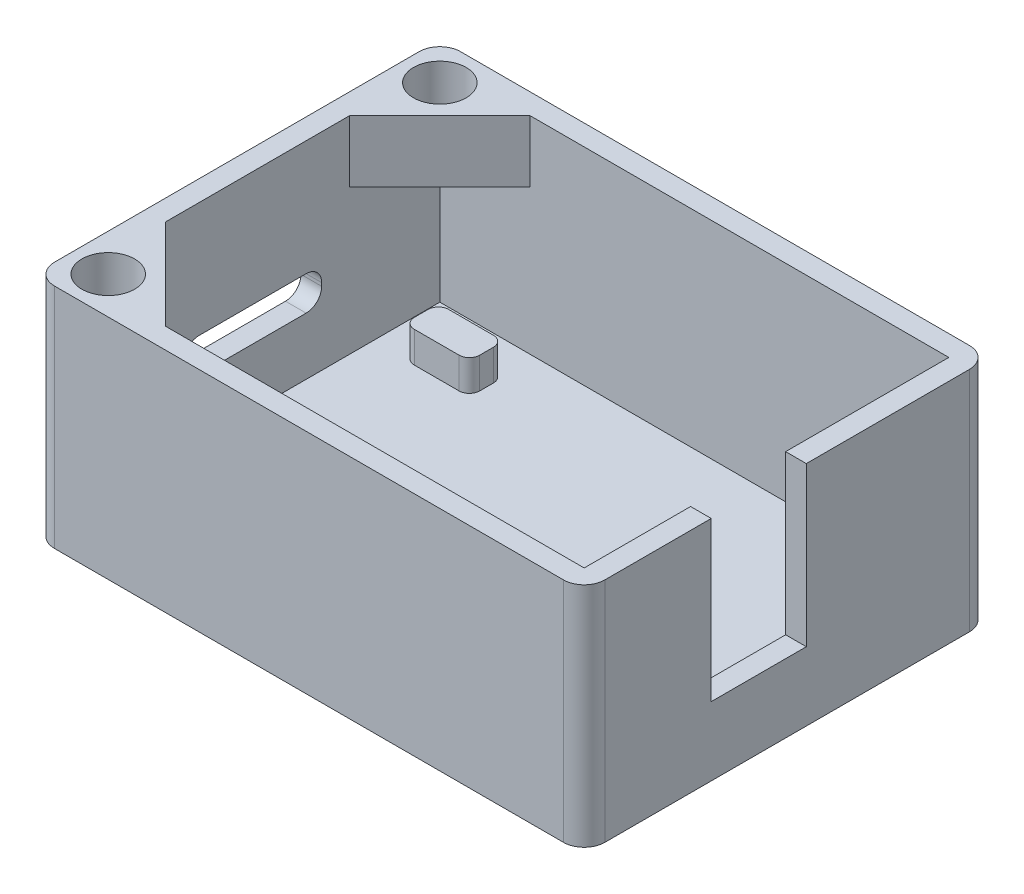
SolidWorks part; units mm, degrees
ref_plane "Front Plane" through (0, 0, 0) normal (0, 0, 1) x (1, 0, 0)
ref_plane "Top Plane" through (0, 0, 0) normal (0, 1, 0) x (1, 0, 0)
ref_plane "Right Plane" through (0, 0, 0) normal (1, 0, 0) x (0, 0, -1)
sketch "Sketch1" plane through (0, 0, 0) normal (0, 1, 0) x (1, 0, 0)
  line L0 (-26.63, 19.645) -> (26.63, 19.645)
  line L1 (-24.13, 17.145) -> (24.13, 17.145) construction
  line L2 (-24.13, 17.145) -> (-24.13, -17.145) construction
  line L3 (-24.13, -17.145) -> (24.13, -17.145) construction
  line L4 (24.13, 17.145) -> (24.13, -17.145) construction
  line L5 (-24.13, 17.145) -> (24.13, -17.145) construction
  line L6 (-24.13, -17.145) -> (24.13, 17.145) construction
  line L7 (26.63, 19.645) -> (26.63, -19.645)
  line L8 (-26.63, -19.645) -> (26.63, -19.645)
  line L9 (-26.63, 19.645) -> (-26.63, -19.645)
  point P0 (0, 0)
  dimension "D1" = 48.26
  dimension "D2" = 34.29
  dimension "D3" = 2.5
extrude "Boss-Extrude1" add sketch "Sketch1" along normal blind 2
sketch "Sketch2" plane through (0, 2, 0) normal (0, 1, 0) x (1, 0, 0)
  line L0 (-24.63, 17.645) -> (24.63, 17.645)
  line L1 (-26.63, 19.645) -> (26.63, 19.645)
  line L2 (-26.63, 19.645) -> (-26.63, -19.645)
  line L3 (-26.63, -19.645) -> (26.63, -19.645)
  line L4 (26.63, 19.645) -> (26.63, -19.645)
  line L5 (-26.63, 19.645) -> (26.63, -19.645) construction
  line L6 (-26.63, -19.645) -> (26.63, 19.645) construction
  line L7 (24.63, 17.645) -> (24.63, -17.645)
  line L8 (-24.63, -17.645) -> (24.63, -17.645)
  line L9 (-24.63, 17.645) -> (-24.63, -17.645)
  point P0 (0, 0)
  dimension "D1" = 2
extrude "Boss-Extrude2" add sketch "Sketch2" along normal blind 20
sketch "Sketch3" plane through (0, 2, 0) normal (0, 1, 0) x (1, 0, 0)
  line L0 (0, 26.1513) -> (0, -23.4046) construction
  line L1 (-20.59, 14.4658) -> (-16.261, 14.4658)
  line L2 (-21.59, 13.4658) -> (-21.59, 12.1374)
  line L3 (-20.59, 11.1374) -> (-16.261, 11.1374)
  line L4 (-15.261, 13.4658) -> (-15.261, 12.1374)
  line L5 (15.261, 13.4658) -> (15.261, 12.1374)
  line L6 (20.59, 11.1374) -> (16.261, 11.1374)
  line L7 (21.59, 13.4658) -> (21.59, 12.1374)
  line L8 (20.59, 14.4658) -> (16.261, 14.4658)
  arc A2 (-21.59, 12.1374) -> (-20.59, 11.1374) centre (-20.59, 12.1374) ccw
  arc A3 (-16.261, 14.4658) -> (-15.261, 13.4658) centre (-16.261, 13.4658) cw
  arc A4 (-15.261, 12.1374) -> (-16.261, 11.1374) centre (-16.261, 12.1374) cw
  arc A5 (-21.59, 13.4658) -> (-20.59, 14.4658) centre (-20.59, 13.4658) cw
  arc A6 (21.59, 13.4658) -> (20.59, 14.4658) centre (20.59, 13.4658) ccw
  arc A7 (15.261, 12.1374) -> (16.261, 11.1374) centre (16.261, 12.1374) ccw
  arc A8 (16.261, 14.4658) -> (15.261, 13.4658) centre (16.261, 13.4658) ccw
  arc A9 (21.59, 12.1374) -> (20.59, 11.1374) centre (20.59, 12.1374) cw
  circle A10 centre (21.844, -14.732) radius 2
  circle A11 centre (-21.59, -14.732) radius 2
  dimension "D1" = 1
extrude "Boss-Extrude3" add sketch "Sketch3" along normal blind 3
sketch "Sketch5" plane through (0, 5, 0) normal (0, 1, 0) x (1, 0, 0)
  circle A2 centre (-21.59, -14.732) radius 1.45
  circle A3 centre (21.844, -14.732) radius 1.45
extrude "Boss-Extrude4" add sketch "Sketch5" along normal blind 1.6
sketch "Sketch6" plane through (26.63, 0, 0) normal (1, 0, 0) x (0, 0, -1)
  line L0 (-19.645, 22) -> (19.645, 22) construction
  line L5 (1.852, 6.65) -> (-7.348, 6.65)
  line L6 (1.852, 6.65) -> (1.852, 22)
  line L7 (1.852, 22) -> (-7.348, 22)
  line L8 (-7.348, 6.65) -> (-7.348, 22)
extrude "Cut-Extrude1" cut sketch "Sketch6" against normal up to next
sketch "Sketch7" plane through (0, 22, 0) normal (0, 1, 0) x (1, 0, 0)
  line L0 (-26.63, 19.645) -> (-13.9021, 19.645)
  line L1 (-26.63, 19.645) -> (-26.63, 6.9171)
  line L2 (0, 0) -> (-26.63, 0) construction
  line L3 (-26.63, 19.645) -> (-26.63, -19.645) construction
  line L4 (-13.9021, 19.645) -> (-26.63, 6.9171)
  line L5 (0, 21.6816) -> (0, -21.9861) construction
  line L9 (-26.63, -19.645) -> (-13.9021, -19.645)
  line L10 (-26.63, -19.645) -> (-26.63, -6.9171)
  line L11 (-13.9021, -19.645) -> (-26.63, -6.9171)
  dimension "D1" = 9
extrude "Boss-Extrude5" add sketch "Sketch7" against normal blind 6
sketch "Sketch8" plane through (0, 22, 0) normal (0, 1, 0) x (1, 0, 0)
  line L0 (0, 0) -> (-26.63, 0) construction
  line L1 (-26.63, 19.645) -> (-26.63, -19.645) construction
  line L2 (26.63, 19.645) -> (-26.63, 19.645) construction
  circle A0 centre (-23.03, 16.045) radius 2.55
  circle A1 centre (-23.03, -16.045) radius 2.55
  dimension "D1" = 5.1
  dimension "D2" = 3.6
  dimension "D3" = 3.6
extrude "Cut-Extrude2" cut sketch "Sketch8" against normal blind 4.2
sketch "Sketch9" plane through (-26.63, 0, 0) normal (-1, 0, 0) x (0, 0, 1)
  line L0 (0.468, 9.2043) -> (11.0029, 9.2043) construction
  line L1 (0.468, 9.2043) -> (0.468, 12.0004) construction
  line L7 (-6.207, 10.8585) -> (7.143, 10.8585)
  line L8 (-6.207, 10.8585) -> (-6.207, 7.55)
  line L9 (-6.207, 7.55) -> (7.143, 7.55)
  line L10 (7.143, 10.8585) -> (7.143, 7.55)
  line L11 (-6.207, 10.8585) -> (7.143, 7.55) construction
  line L12 (-6.207, 7.55) -> (7.143, 10.8585) construction
extrude "Cut-Extrude3" cut sketch "Sketch9" against normal up to next
fillet "Fillet2" radius 2 4 edges at (26.63, 11, -19.645) (26.63, 11, 19.645) (-26.63, 11, -19.645) (-26.63, 11, 19.645)
fillet "Fillet3" radius 1.5 4 edges at (-25.63, 10.8585, -6.207) (-25.63, 7.55, -6.207) (-25.63, 7.55, 7.143) (-25.63, 10.8585, 7.143)
sketch "Sketch10" plane through (0, 0, 0) normal (0, -1, 0) x (-1, 0, 0)
  text T0 "<b>Cloudlight</b>\r\n<b>MR-Addict</b>" font "Century Gothic" height 6
extrude "Cut-Extrude4" cut sketch "Sketch10" against normal blind 1
